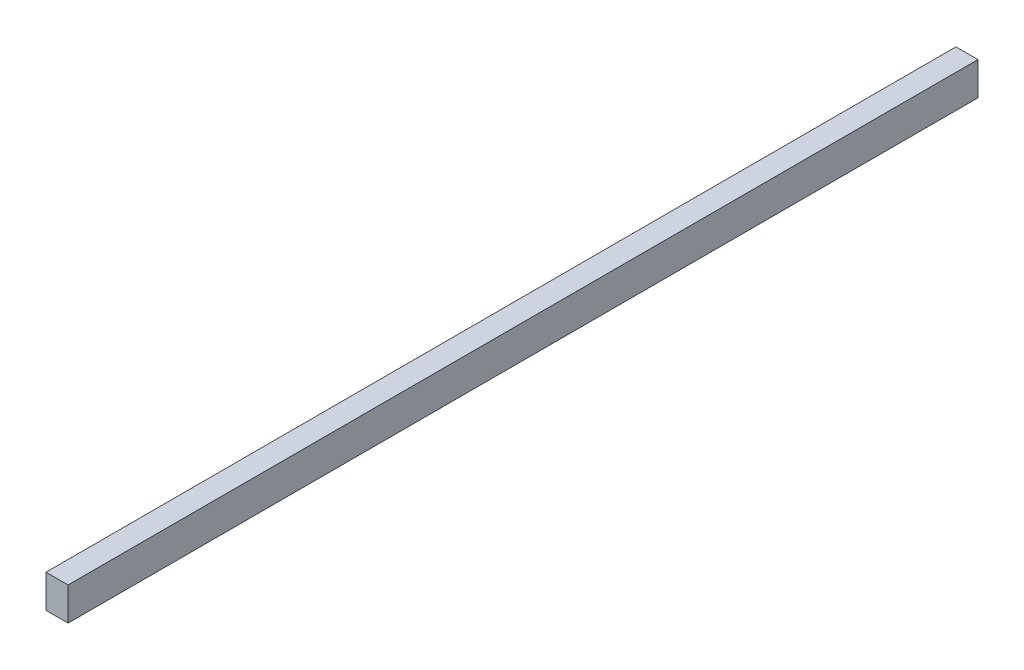
SolidWorks part; units mm, degrees
ref_plane "Front Plane" through (0, 0, 0) normal (0, 0, 1) x (1, 0, 0)
ref_plane "Top Plane" through (0, 0, 0) normal (0, 1, 0) x (1, 0, 0)
ref_plane "Right Plane" through (0, 0, 0) normal (1, 0, 0) x (0, 0, -1)
sketch "Sketch1" plane through (0, 0, 0) normal (1, 0, 0) x (0, 0, -1)
  line L1 (0, 0) -> (495, 0)
  line L2 (0, 0) -> (0, 18)
  line L3 (0, 18) -> (495, 18)
  line L4 (495, 0) -> (495, 18)
  dimension "D1" = 495
  dimension "D2" = 18
extrude "Boss-Extrude1" add sketch "Sketch1" along normal blind 12
